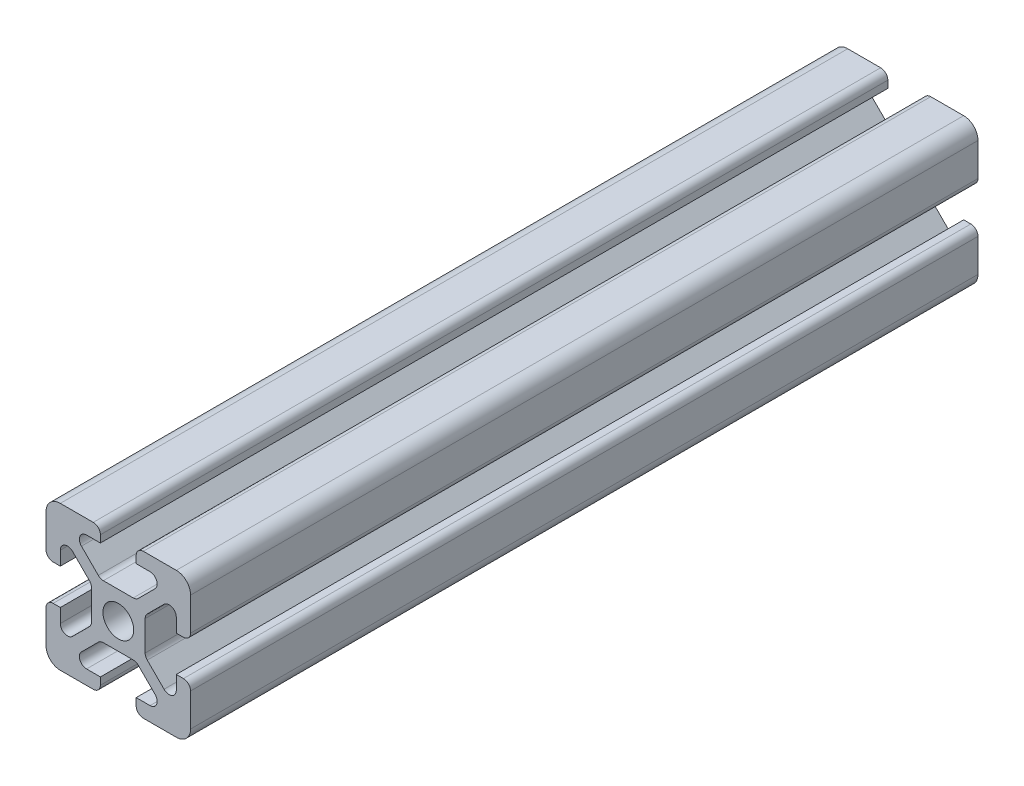
SolidWorks part; units mm, degrees
ref_plane "Front Plane" through (0, 0, 0) normal (0, 0, 1) x (1, 0, 0)
ref_plane "Top Plane" through (0, 0, 0) normal (0, 1, 0) x (1, 0, 0)
ref_plane "Right Plane" through (0, 0, 0) normal (1, 0, 0) x (0, 0, -1)
sketch "Sketch1" plane through (0, 0, 0) normal (0, 0, 1) x (1, 0, 0)
  line L0 (10.1, 10) -> (10.1, 0.1) construction
  line L1 (2, 0) -> (6.6, 0)
  line L2 (0, 2) -> (0, 6.6)
  line L3 (2, 20.2) -> (6.6, 20.2)
  line L4 (20.2, 2) -> (20.2, 6.6)
  line L5 (10.1, 10) -> (0, 10) construction
  line L6 (7.6, 19.2) -> (7.6, 18.2)
  line L7 (7.6, 18.2) -> (5.6642, 18.2)
  line L8 (4.9571, 16.4929) -> (7.3071, 14.1429)
  line L9 (8.0142, 13.85) -> (12.1858, 13.85)
  line L10 (12.8929, 14.1429) -> (15.2429, 16.4929)
  line L11 (14.5358, 18.2) -> (12.6, 18.2)
  line L12 (12.6, 18.2) -> (12.6, 19.2)
  line L13 (-250.157, -110.88) -> (53.1764, -110.88) construction
  line L14 (13.6, 20.2) -> (18.2, 20.2)
  line L15 (19.2, 12.6) -> (18.2, 12.6)
  line L16 (18.2, 12.6) -> (18.2, 14.5358)
  line L17 (16.4929, 15.2429) -> (14.1429, 12.8929)
  line L18 (13.85, 12.1858) -> (13.85, 8.0142)
  line L19 (14.1429, 7.3071) -> (16.4929, 4.9571)
  line L20 (18.2, 5.6642) -> (18.2, 7.6)
  line L21 (18.2, 7.6) -> (19.2, 7.6)
  line L22 (12.6, 1) -> (12.6, 2)
  line L23 (12.6, 2) -> (14.5358, 2)
  line L24 (15.2429, 3.7071) -> (12.8929, 6.0571)
  line L25 (12.1858, 6.35) -> (8.0142, 6.35)
  line L26 (7.3071, 6.0571) -> (4.9571, 3.7071)
  line L27 (5.6642, 2) -> (7.6, 2)
  line L28 (7.6, 2) -> (7.6, 1)
  line L29 (1, 7.6) -> (2, 7.6)
  line L30 (2, 7.6) -> (2, 5.6642)
  line L31 (3.7071, 4.9571) -> (6.0571, 7.3071)
  line L32 (6.35, 8.0142) -> (6.35, 12.1858)
  line L33 (6.0571, 12.8929) -> (3.7071, 15.2429)
  line L34 (2, 14.5358) -> (2, 12.6)
  line L35 (2, 12.6) -> (1, 12.6)
  line L36 (20.2, 13.6) -> (20.2, 18.2)
  line L37 (13.6, 0) -> (18.2, 0)
  line L38 (0, 13.6) -> (0, 18.2)
  circle A0 centre (10.1, 10) radius 2.15
  arc A1 (12.8929, 14.1429) -> (12.1858, 13.85) centre (12.1858, 14.85) cw
  arc A2 (8.0142, 13.85) -> (7.3071, 14.1429) centre (8.0142, 14.85) cw
  arc A3 (15.2429, 16.4929) -> (14.5358, 18.2) centre (14.5358, 17.2) ccw
  arc A4 (5.6642, 18.2) -> (4.9571, 16.4929) centre (5.6642, 17.2) ccw
  arc A5 (2, 0) -> (0, 2) centre (2, 2) cw
  arc A6 (18.2, 0) -> (20.2, 2) centre (18.2, 2) ccw
  arc A7 (20.2, 18.2) -> (18.2, 20.2) centre (18.2, 18.2) ccw
  arc A8 (2, 20.2) -> (0, 18.2) centre (2, 18.2) ccw
  arc A9 (18.2, 14.5358) -> (16.4929, 15.2429) centre (17.2, 14.5358) ccw
  arc A10 (13.85, 12.1858) -> (14.1429, 12.8929) centre (14.85, 12.1858) cw
  arc A11 (14.1429, 7.3071) -> (13.85, 8.0142) centre (14.85, 8.0142) cw
  arc A12 (16.4929, 4.9571) -> (18.2, 5.6642) centre (17.2, 5.6642) ccw
  arc A13 (14.5358, 2) -> (15.2429, 3.7071) centre (14.5358, 3) ccw
  arc A14 (12.1858, 6.35) -> (12.8929, 6.0571) centre (12.1858, 5.35) cw
  arc A15 (7.3071, 6.0571) -> (8.0142, 6.35) centre (8.0142, 5.35) cw
  arc A16 (4.9571, 3.7071) -> (5.6642, 2) centre (5.6642, 3) ccw
  arc A17 (2, 5.6642) -> (3.7071, 4.9571) centre (3, 5.6642) ccw
  arc A18 (6.35, 8.0142) -> (6.0571, 7.3071) centre (5.35, 8.0142) cw
  arc A19 (6.0571, 12.8929) -> (6.35, 12.1858) centre (5.35, 12.1858) cw
  arc A20 (3.7071, 15.2429) -> (2, 14.5358) centre (3, 14.5358) ccw
  arc A21 (20.2, 13.6) -> (19.2, 12.6) centre (19.2, 13.6) cw
  arc A22 (20.2, 6.6) -> (19.2, 7.6) centre (19.2, 6.6) ccw
  arc A23 (13.6, 0) -> (12.6, 1) centre (13.6, 1) cw
  arc A24 (7.6, 1) -> (6.6, 0) centre (6.6, 1) cw
  arc A25 (1, 7.6) -> (0, 6.6) centre (1, 6.6) ccw
  arc A26 (1, 12.6) -> (0, 13.6) centre (1, 13.6) cw
  arc A27 (7.6, 19.2) -> (6.6, 20.2) centre (6.6, 19.2) ccw
  arc A28 (13.6, 20.2) -> (12.6, 19.2) centre (13.6, 19.2) ccw
  point P21 (12.6, 13.85)
  point P24 (7.6, 13.85)
  point P31 (0, 0)
  point P36 (20.2, 20.2)
  point P39 (0, 20.2)
  point P91 (10.1, 10.1)
  point P105 (12.6, 20.2)
  dimension "D3" = 4.3
  dimension "D9" = 1
  dimension "D10" = 2
  dimension "D13" = 1
  dimension "D1" = 20.2
  dimension "D2" = 10.1
  dimension "D4" = 5
  dimension "D5" = 2.5
  dimension "D6" = 6.35
  dimension "D7" = 2
  dimension "D8" = 45
  dimension "D12" = 10
  dimension "D14" = 20.2
  dimension "D15" = 7.6
  dimension "D16" = 6.35
  dimension "D11" = 4
extrude "Boss-Extrude1" add sketch "Sketch1" along normal blind 110
